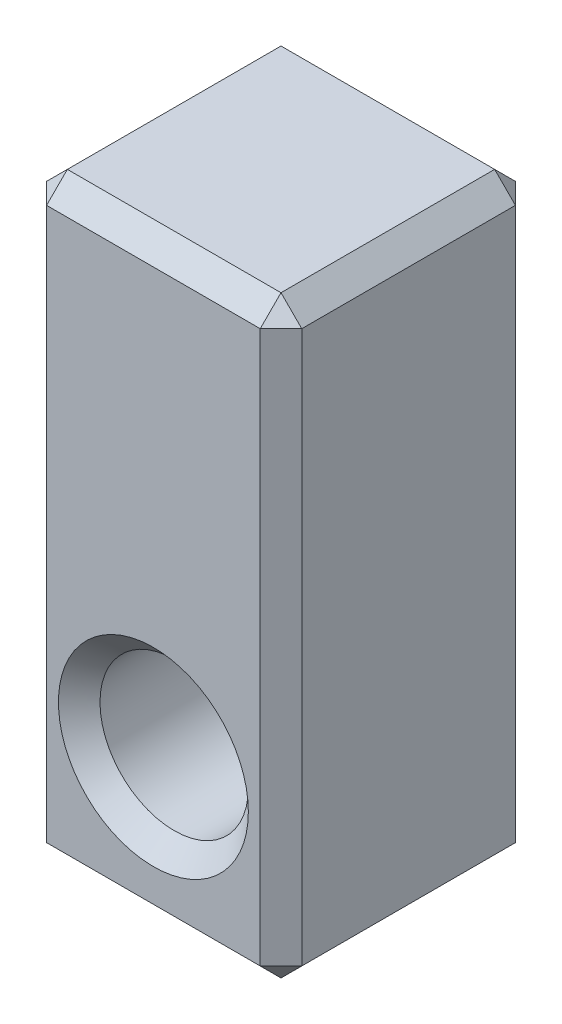
SolidWorks part; units mm, degrees
ref_plane "Front Plane" through (0, 0, 0) normal (0, 0, 1) x (1, 0, 0)
ref_plane "Top Plane" through (0, 0, 0) normal (0, 1, 0) x (1, 0, 0)
ref_plane "Right Plane" through (0, 0, 0) normal (1, 0, 0) x (0, 0, -1)
sketch "Sketch1" plane through (0, 0, 0) normal (0, 1, 0) x (1, 0, 0)
  line L0 (-41.5745, 21.3069) -> (-41.5745, -0.5371)
  line L9 (-41.5745, -0.5371) -> (-19.7305, -0.5371)
  line L10 (-19.7305, -0.5371) -> (-19.7305, 21.3069)
  line L11 (-19.7305, 21.3069) -> (-41.5745, 21.3069)
  dimension "D1" = 21.844
extrude "Boss-Extrude1" add sketch "Sketch1" along normal blind 50.8
sketch "Sketch3" plane through (0, 0, 0.5371) normal (0, 0, 1) x (1, 0, 0)
  line L0 (-41.5745, 50.8) -> (-41.5745, 0) construction
  line L1 (-41.5745, 0) -> (-19.7305, 0) construction
  circle A5 centre (-30.6525, 12.7) radius 6.35
  point P2 (0, 0)
  dimension "D3" = 12.7
  dimension "D1" = 12.7
  dimension "D2" = 10.922
extrude "Cut-Extrude2" cut sketch "Sketch3" against normal through all
chamfer "Chamfer1" distance 1.778 angle 45 14 edges at (-24.3025, 12.7, 0.5371) (-24.3025, 12.7, -21.3069) (-30.6525, 0, -21.3069) (-41.5745, 0, -10.3849) (-30.6525, 0, 0.5371) (-19.7305, 0, -10.3849) (-19.7305, 25.4, -21.3069) (-30.6525, 50.8, -21.3069) (-41.5745, 25.4, 0.5371) (-41.5745, 50.8, -10.3849) (-41.5745, 25.4, -21.3069) (-30.6525, 50.8, 0.5371) (-19.7305, 50.8, -10.3849) (-19.7305, 25.4, 0.5371)
